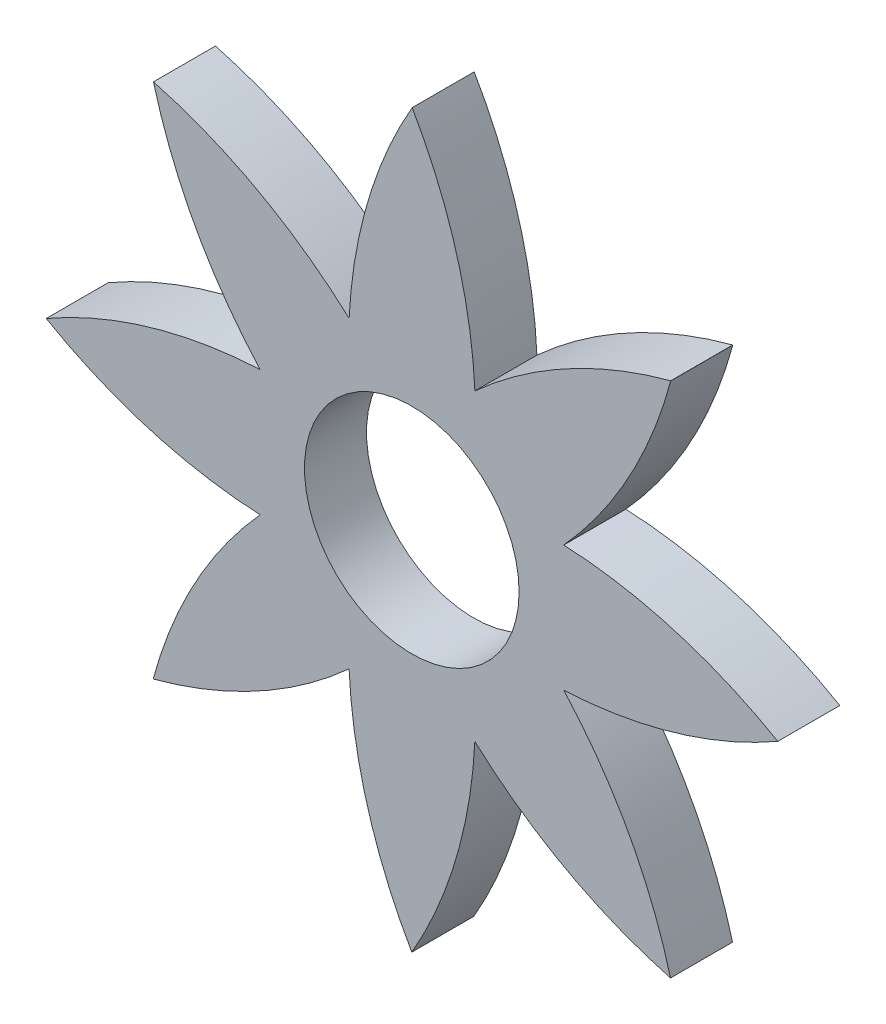
SolidWorks part; units mm, degrees
ref_plane "Front Plane" through (0, 0, 0) normal (0, 0, 1) x (1, 0, 0)
ref_plane "Top Plane" through (0, 0, 0) normal (0, 1, 0) x (1, 0, 0)
ref_plane "Right Plane" through (0, 0, 0) normal (1, 0, 0) x (0, 0, -1)
sketch "Sketch1" plane through (0, 0, 0) normal (0, 0, 1) x (1, 0, 0)
  line L1 (-50.8, -50.8) -> (50.8, -50.8)
  line L2 (-50.8, -50.8) -> (-50.8, 50.8)
  line L3 (-50.8, 50.8) -> (50.8, 50.8)
  line L4 (50.8, -50.8) -> (50.8, 50.8)
  line L5 (-50.8, -50.8) -> (50.8, 50.8) construction
  line L6 (-50.8, 50.8) -> (50.8, -50.8) construction
  circle A0 centre (0, 0) radius 37.465
  circle A1 centre (0, 0) radius 10.9855
  circle A2 centre (0, 0) radius 4.0386
  arc A3 (15.5603, 6.4536) -> (37.465, 0) centre (13.1837, -42.0144) cw
  arc A4 (15.5579, -6.4194) -> (37.465, 0) centre (13.2485, 42.0518) ccw
  arc A5 (15.5579, -6.4194) -> (26.4835, -26.4718) centre (-20.3946, -39.0109) cw
  arc A6 (6.4536, -15.5203) -> (26.4835, -26.4718) centre (39.0949, 20.387) ccw
  arc A7 (6.4536, -15.5203) -> (0, -37.4251) centre (-42.0144, -13.1437) cw
  arc A8 (-6.4194, -15.5179) -> (0, -37.4251) centre (42.0518, -13.2085) ccw
  arc A9 (-6.4194, -15.5179) -> (-26.4718, -26.4435) centre (-39.0109, 20.4346) cw
  arc A10 (-15.5203, -6.4136) -> (-26.4718, -26.4435) centre (20.387, -39.055) ccw
  arc A11 (-15.5203, -6.4136) -> (-37.425, 0.0399) centre (-13.1437, 42.0543) cw
  arc A12 (-15.5179, 6.4594) -> (-37.425, 0.0399) centre (-13.2085, -42.0118) ccw
  arc A13 (-15.5179, 6.4594) -> (-26.4435, 26.5117) centre (20.4346, 39.0509) cw
  arc A14 (-6.4136, 15.5603) -> (-26.4435, 26.5117) centre (-39.0549, -20.3471) ccw
  arc A15 (-6.4136, 15.5603) -> (0.0399, 37.465) centre (42.0543, 13.1837) cw
  arc A16 (6.4594, 15.5579) -> (0.0399, 37.465) centre (-42.0118, 13.2484) ccw
  arc A17 (6.4594, 15.5579) -> (26.5117, 26.4835) centre (39.0509, -20.3947) cw
  arc A18 (15.5603, 6.4536) -> (26.5117, 26.4835) centre (-20.347, 39.0949) ccw
  point P0 (0, 0)
  point P53 (0.02, 0.02)
  point P69 (0, 0)
  dimension "D3" = 74.93
  dimension "D4" = 21.971
  dimension "D5" = 8.0772
  dimension "D9" = 16.8086
  dimension "D11" = 48.5262
  dimension "D1" = 101.6
  dimension "D2" = 101.6
  dimension "D7" = 37.465
  dimension "D8" = 12.873
  dimension "D10" = 35.6732
  dimension "D6" = 8
extrude "Boss-Extrude1" add sketch "Sketch1" along normal blind 6.35 contours A3 A18 A0 A17 A16 A15 A14 A13 A12 A11 A10 A9 A8 A7 A6 A5 A4 A1
